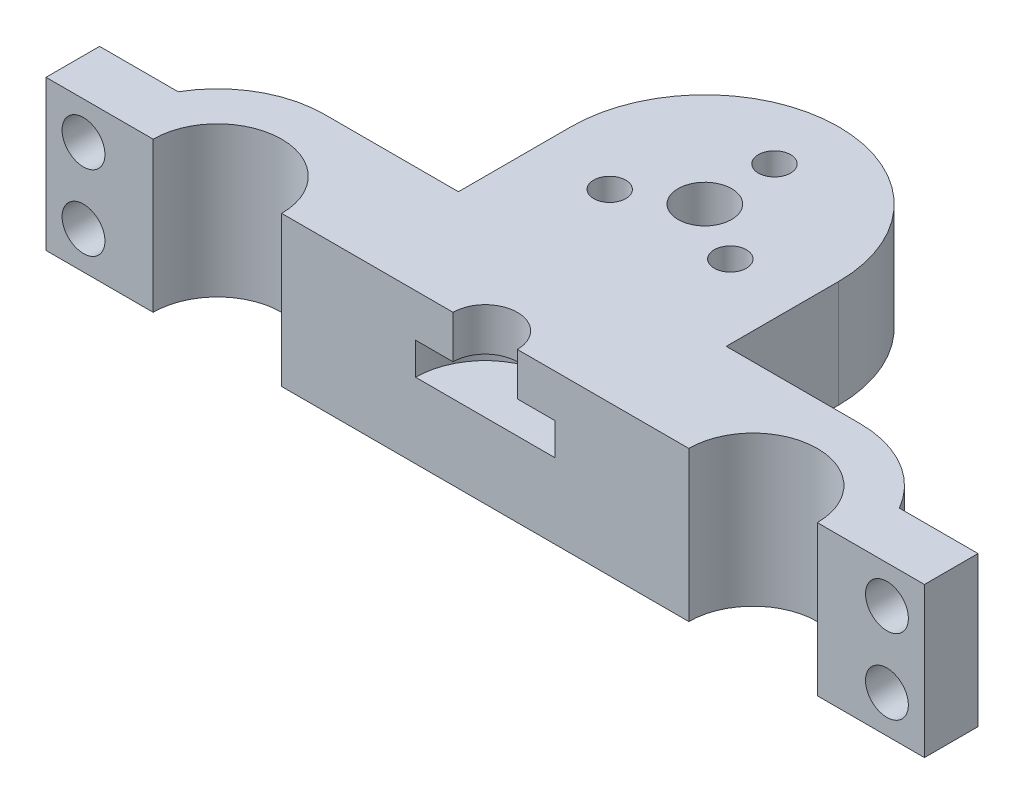
SolidWorks part; units mm, degrees
ref_plane "Front Plane" through (0, 0, 0) normal (0, 0, 1) x (1, 0, 0)
ref_plane "Top Plane" through (0, 0, 0) normal (0, 1, 0) x (1, 0, 0)
ref_plane "Right Plane" through (0, 0, 0) normal (1, 0, 0) x (0, 0, -1)
sketch "Sketch2" plane through (0, 0, 0) normal (0, 1, 0) x (1, 0, 0)
  line L0 (-3, 0) -> (-19, 0)
  line L1 (3, 0) -> (19, 0)
  line L2 (-31, 0) -> (-41, 0)
  line L3 (31, 0) -> (41, 0)
  line L4 (-41, 0) -> (-41, 5)
  line L5 (41, 0) -> (41, 5)
  line L6 (-25, 10) -> (25, 10)
  line L7 (-41, 5) -> (-33.6603, 5)
  line L8 (41, 5) -> (33.6603, 5)
  arc A1 (-19, 0) -> (-31, 0) centre (-25, 0) ccw
  arc A2 (31, 0) -> (19, 0) centre (25, 0) ccw
  arc A3 (3, 0) -> (-3, 0) centre (0, 0) ccw
  arc A4 (-25, 10) -> (-33.6603, 5) centre (-25, 0) ccw
  arc A5 (33.6603, 5) -> (25, 10) centre (25, 0) ccw
  dimension "D2" = 12
  dimension "D3" = 12
  dimension "D4" = 6
  dimension "D12" = 20
  dimension "D5" = 16
  dimension "D6" = 16
  dimension "D7" = 10
  dimension "D8" = 10
  dimension "D9" = 5
  dimension "D10" = 5
  dimension "D11" = 10
extrude "Boss-Extrude1" add sketch "Sketch2" along normal blind 14
sketch "Sketch4" plane through (0, 0, 0) normal (0, 0, 1) x (1, 0, 0)
  line L1 (-41, 0) -> (-31, 0) construction
  line L3 (-41, 14) -> (-41, 0) construction
  line L4 (41, 14) -> (41, 0) construction
  circle A0 centre (-37.5, 10.5) radius 2
  circle A1 centre (-37.5, 3.5) radius 2
  circle A2 centre (37.5, 10.5) radius 2
  circle A3 centre (37.5, 3.5) radius 2
  point P12 (0, 0)
  point P13 (0, 0)
  dimension "D1" = 4
  dimension "D2" = 4
  dimension "D4" = 3.5
  dimension "D6" = 4
  dimension "D7" = 4
  dimension "D3" = 7
  dimension "D5" = 3.5
  dimension "D8" = 7
  dimension "D9" = 3.5
extrude "Cut-Extrude1" cut sketch "Sketch4" against normal through all both and the other way through all
sketch "Sketch5" plane through (0, 0, 0) normal (0, -1, 0) x (1, 0, 0)
  line L0 (-4.6833, 0) -> (4.6254, 0)
  line L1 (-19, 0) -> (-3, 0) construction
  line L2 (3, 0) -> (19, 0) construction
  line L3 (4.6254, 0) -> (4.6254, -4.0444)
  line L4 (4.6254, -4.0444) -> (-4.6833, -4.0444)
  line L5 (-4.6833, -4.0444) -> (-4.6833, 0)
  point P7 (0, 0)
  point P9 (0, 0)
  point P10 (0, 0)
  point P11 (0, 0)
  dimension "D1" = 9.3087
  dimension "D2" = 4.0444
  dimension "D3" = 14.3167
extrude "Boss-Extrude2" add sketch "Sketch5" against normal blind 7
sketch "Sketch6" plane through (0, 7, 0) normal (0, 1, 0) x (1, 0, 0)
  circle A0 centre (0, 0) radius 6.5
  dimension "D1" = 13
extrude "Cut-Extrude2" cut sketch "Sketch6" against normal mid plane 3 from offset 1.5
sketch "Sketch7" plane through (0, 14, 0) normal (0, 1, 0) x (1, 0, 0)
  line L0 (-12.5, 20.5) -> (-12.5, 10)
  line L1 (25, 10) -> (-25, 10) construction
  line L2 (12.5, 20.5) -> (12.5, 10)
  line L3 (-12.5, 10) -> (12.5, 10)
  arc A0 (12.5, 20.5) -> (-12.5, 20.5) centre (0, 20.5) ccw
  dimension "D1" = 25
  dimension "D2" = 20.5
extrude "Boss-Extrude3" add sketch "Sketch7" against normal blind 10
sketch "Sketch8" plane through (0, 4, 0) normal (0, -1, 0) x (1, 0, 0)
  circle A0 centre (0, -20.5) radius 10
  dimension "D1" = 20
extrude "Cut-Extrude3" cut sketch "Sketch8" against normal blind 4
sketch "Sketch9" plane through (0, 8, 0) normal (0, -1, 0) x (1, 0, 0)
  circle A0 centre (0, -20.5) radius 2.5
  dimension "D1" = 5
extrude "Cut-Extrude4" cut sketch "Sketch9" against normal through all
sketch "Sketch10" plane through (0, 8, 0) normal (0, -1, 0) x (1, 0, 0)
  circle A0 centre (0, -27) radius 1.5
  circle A1 centre (0, -20.5) radius 2.5 construction
  circle A2 centre (-5.6292, -17.25) radius 1.5
  circle A3 centre (5.6292, -17.25) radius 1.5
  point P4 (0, 0)
  point P5 (0, -27)
  point P6 (0, 0)
  point P11 (0, -20.5)
  point P13 (0, -27)
  dimension "D1" = 3
  dimension "D2" = 6.5
  dimension "D4" = 20.5
  dimension "D3" = 3
extrude "Cut-Extrude5" cut sketch "Sketch10" against normal through all
